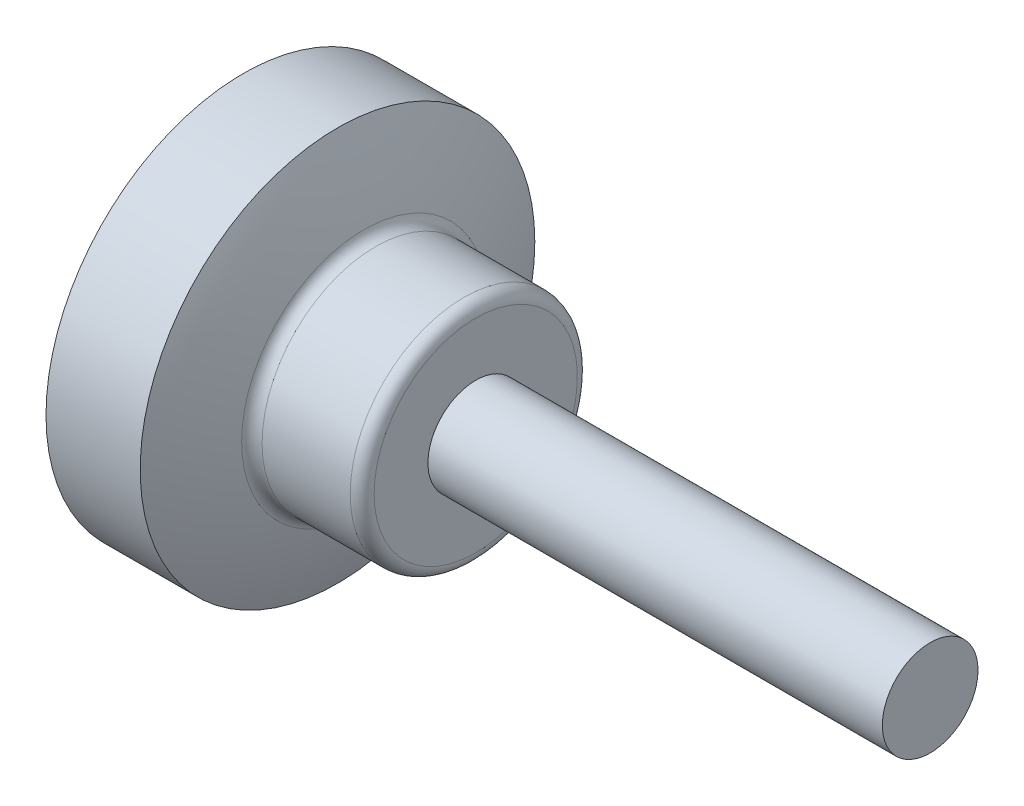
SolidWorks part; units mm, degrees
ref_plane "Front Plane" through (0, 0, 0) normal (0, 0, 1) x (1, 0, 0)
ref_plane "Top Plane" through (0, 0, 0) normal (0, 1, 0) x (1, 0, 0)
ref_plane "Right Plane" through (0, 0, 0) normal (1, 0, 0) x (0, 0, -1)
sketch "Sketch1" plane through (0, 0, 0) normal (0, 1, 0) x (1, 0, 0)
  line L0 (0, 0) -> (82.8801, 0) construction
  line L1 (3.5617, 16.5) -> (3.5617, 0) construction
  line L2 (3.5617, 16.5) -> (11.4383, 16.5)
  line L3 (23, 0) -> (23, 8.5)
  line L4 (22, 9.5) -> (14.6327, 9.5)
  line L5 (0, 0) -> (23, 0)
  arc A0 (0, 0) -> (3.5617, 16.5) centre (40, 0) cw
  arc A1 (11.4383, 16.5) -> (13.666, 10.2439) centre (-25, 0) cw
  arc A2 (13.666, 10.2439) -> (14.6327, 9.5) centre (14.6327, 10.5) ccw
  arc A3 (23, 8.5) -> (22, 9.5) centre (22, 8.5) ccw
  dimension "D2" = 40
  dimension "D3" = 40
  dimension "D5" = 1
  dimension "D7" = 1
  dimension "D1" = 16.5
  dimension "D4" = 9.5
  dimension "D6" = 23
revolve "Revolve1" add sketch "Sketch1" angle 360 about L5
sketch "Sketch2" plane through (23, 0, 0) normal (1, 0, 0) x (0, 0, -1)
  circle A0 centre (0, 0) radius 4
  dimension "D1" = 8
extrude "Boss-Extrude1" add sketch "Sketch2" along normal blind 38 separate body
